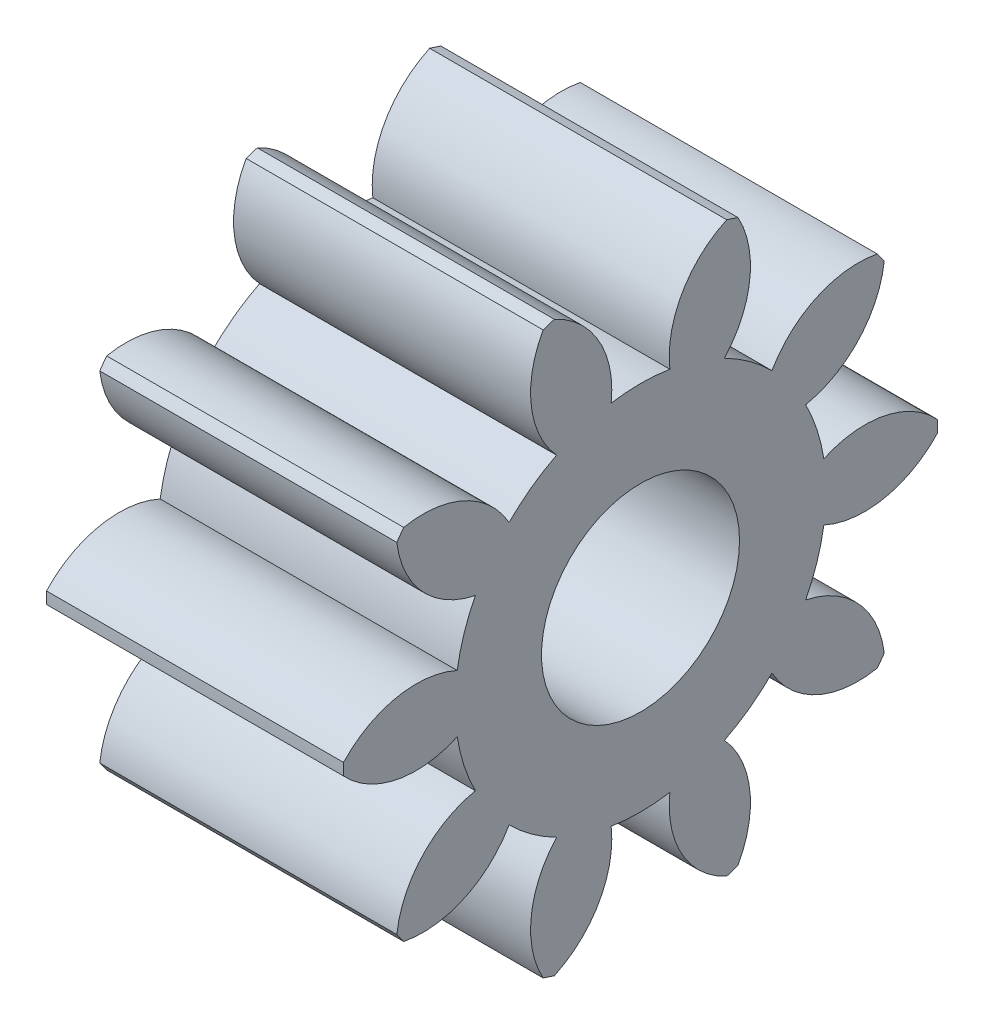
SolidWorks part; units mm, degrees
ref_plane "Plane1" through (0, 0, 0) normal (0, 0, 1) x (1, 0, 0)
ref_plane "Plane2" through (0, 0, 0) normal (0, 1, 0) x (1, 0, 0)
ref_plane "Plane3" through (0, 0, 0) normal (1, 0, 0) x (0, 0, -1)
sketch "HoldingSke" plane through (0, 0, 0) normal (0, 1, 0) x (1, 0, 0)
  line L0 (0, 0) -> (1.9696, -0.3473)
  line L1 (-15, 0) -> (100, 0) construction
  line L2 (0, 0) -> (-2.1039, 2.3779)
  line L3 (0, 0) -> (-11.863, 4.5341)
  line L4 (0, 0) -> (8.5048, 1.4996)
  line L5 (0, 0) -> (-46.8476, -17.4728)
  line L6 (0, 0) -> (-9.9476, -6.7116)
  line L7 (-2.1039, 2.3779) -> (8.6586, 51.2059)
  line L8 (-76.2, 54.61) -> (-75.9, 54.61)
  line L9 (-71.009, 38.7566) -> (-53.1078, 45.2721)
  line L10 (-76.2, 71.12) -> (104.1128, 71.12)
  line L11 (0, 0) -> (-12, 0)
  line L12 (-76.2, 101.6) -> (-76.181, 101.6)
  line L13 (24.9733, 27.94) -> (52.9518, 28.4284)
  line L14 (24.9733, 27.94) -> (24.9743, 27.94)
  line L15 (24.9733, 27.94) -> (100.4006, 29.5858)
  line L16 (-63.627, -0.5) -> (-12.827, -0.5)
  circle A0 centre (0, 0) radius 1
  circle A1 centre (0, 0) radius 1.874
  circle A2 centre (0, 0) radius 37.5
  circle A3 centre (0, 0) radius 1
  dimension "MHD" = 3.748
  dimension "Hub_dia" = 75
  dimension "Bore" = 2
  dimension "MBD" = 2
  dimension "Num_teeth" = 10
  dimension "Pitch" = 2
  dimension "Overall_len" = 50
  dimension "Show_teeth" = 10
  dimension "Thickness" = 12
  dimension "OAL" = 50.0001
  dimension "T_dim" = 0.3
  dimension "Ap" = 20
  dimension "H" = 19.05
  dimension "Pitch_radius" = 180.3128
  dimension "Width" = 12
  dimension "Backlash" = 0.019
  dimension "Addendum_fac" = 1
  dimension "Dedendum_fac" = 1.25
  dimension "Clearance_fac" = 0.25
  dimension "Dedendum_add" = 0.001
  dimension "Module" = 0.5
sketch "BasProSke" plane through (0, 0, 0) normal (0, 1, 0) x (1, 0, 0)
  line L0 (-10, 0) -> (60, 0) construction
  line L1 (0, 0) -> (0, 3)
  line L2 (0, 0) -> (12, 0)
  line L3 (12, 0) -> (12, 3)
  line L4 (12, 3) -> (0, 3)
  dimension "Thickness" = 12
  dimension "Diameter" = 6
revolve "Base-Revolve" add sketch "BasProSke" angle 360 about L0
sketch "TooCutSke" plane through (0, 0, 0) normal (1, 0, 0) x (0, 0, -1)
  line L1 (0, 0) -> (0, 107) construction
  line L2 (0, 0) -> (-0.4243, 2.4637) construction
  line L3 (0, 0) -> (-1.5292, 4.7063) construction
  line L4 (-0.4243, 2.4637) -> (-0.7646, 2.3532) construction
  arc A0 (0.2964, 1.8504) -> (-0.2964, 1.8504) centre (0, 0) ccw
  arc A1 (0.9059, 2.8866) -> (-0.9059, 2.8866) centre (0, 0) ccw
  circle A2 centre (0, 0) radius 2.5 construction
  circle A3 centre (0, 0) radius 2.3492 construction
  arc A4 (-0.2964, 1.8504) -> (-0.9059, 2.8866) centre (-1.2901, 1.9633) ccw
  arc A5 (0.9059, 2.8866) -> (0.2964, 1.8504) centre (1.2901, 1.9633) ccw
  dimension "Root_dia" = 3.748
  dimension "Overcut_dia" = 6.0508
  dimension "Pitch_dia" = 5
  dimension "Base_dia" = 4.6985
  dimension "Flank_rad" = 1
  dimension "Half_ang" = 18
  dimension "Half_CT" = 0.3578
extrude "ToothCut" cut sketch "TooCutSke" along normal through all
fillet "Breaks" [suppressed] radius 0.01
fillet "RootFillets" [suppressed] radius 0.126
pattern_circular "TeethCuts" count 10 every 36 about axis through (-10, 0, 0) along (1, 0, 0) of "ToothCut", "RootFillets", "Breaks"
sketch "HubNeaOneSke" plane through (0, 0, 0) normal (-1, 0, 0) x (0, 0, 1)
  circle A0 centre (0, 0) radius 1.874
  dimension "Diameter" = 3.748
extrude "HubNearOne" [suppressed] add sketch "HubNeaOneSke" along normal blind 38.0001
sketch "HubNeaBotSke" plane through (0, 0, 0) normal (-1, 0, 0) x (0, 0, 1)
  circle A0 centre (0, 0) radius 1.874
  dimension "Diameter" = 3.748
extrude "HubNearBoth" [suppressed] add sketch "HubNeaBotSke" along normal blind 19
ref_plane "FarPln" through (12, 0, 0) normal (1, 0, 0) x (0, 0, -1)
sketch "HubFarSke" plane through (12, 0, 0) normal (1, 0, 0) x (0, 0, -1)
  circle A0 centre (0, 0) radius 1.874
  dimension "Diameter" = 3.748
extrude "HubFar" [suppressed] add sketch "HubFarSke" along normal blind 19
sketch "BorSke" plane through (0, 0, 0) normal (1, 0, 0) x (0, 0, -1)
  circle A0 centre (0, 0) radius 1
  dimension "Diameter" = 2
extrude "Bore" cut sketch "BorSke" along normal mid plane 100.0001
sketch "KeySke" plane through (0, 0, 0) normal (1, 0, 0) x (0, 0, -1)
  line L0 (-0.4, 0) -> (-0.4, 1.3)
  line L1 (-0.4, 1.3) -> (0.4, 1.3)
  line L2 (0.4, 1.3) -> (0.4, 0)
  line L3 (0, 0) -> (0, 34) construction
  line L4 (-0.4, 0) -> (0.4, 0)
  dimension "Offset" = 1.3
  dimension "Width" = 0.8
extrude "Keyway" [suppressed] cut sketch "KeySke" along normal mid plane 100.0001
pattern_circular "Keyway2" [suppressed] count 2 every 90 about axis through (-10, 0, 0) along (1, 0, 0)
sketch "Croquis1" plane through (12, 0, 0) normal (1, 0, 0) x (0, 0, -1)
  line L1 (-3.594, 3.3455) -> (3.7696, 3.3455)
  line L2 (-3.594, 3.3455) -> (-3.594, -3.2243)
  line L3 (-3.594, -3.2243) -> (3.7696, -3.2243)
  line L4 (3.7696, 3.3455) -> (3.7696, -3.2243)
extrude "Cortar-Extruir1" cut sketch "Croquis1" against normal blind 9
equation "' \"Module@HoldingSke\" = 6.35"
equation "' \"Num_teeth@HoldingSke\" = 12"
equation "' \"Ap@HoldingSke\" =  20"
equation "' \"Ap@HoldingSke\" = 20"
equation "' \"Width@HoldingSke\" = 0.5 * 25.4"
equation "' \"Hub_dia@HoldingSke\"= 1 * 25.4"
equation "' \"Hub_dia@HoldingSke\" = 1 * 25.4"
equation "' \"Overall_len@HoldingSke\" = 1.0 * 25.4"
equation "' \"Bore@HoldingSke\" = 0.75 * 25.4"
equation "' \"T_dim@HoldingSke\" = 0.1 * 25.4"
equation "' \"Width@KeySke\" = 0.25 * 25.4"
equation "' \"Show_teeth@HoldingSke\" = 13"
equation "' \"Backlash@HoldingSke\" = 0.009 * 25.4"
equation "' \"Addendum_fac@HoldingSke\" = 1.0"
equation "' \"Dedendum_fac@HoldingSke\" = 1.25"
equation "' \"Dedendum_add@HoldingSke\" = 0.00005 * 25.4"
equation "' \"Clearance_fac@HoldingSke\" = 0.25"
equation "\"Pitch@HoldingSke\" = 1 / \"Module@HoldingSke\""
equation "\"Overcut_dia@TooCutSke\" = (\"Num_teeth@HoldingSke\" + 2 * \"Addendum_fac@HoldingSke\") / \"Pitch@HoldingSke\" + 0.002 * 25.4"
equation "\"Pitch_dia@TooCutSke\" = \"Num_teeth@HoldingSke\" / \"Pitch@HoldingSke\""
equation "\"Base_dia@TooCutSke\" = \"Num_teeth@HoldingSke\" / \"Pitch@HoldingSke\" * cos((\"Ap@HoldingSke\"  * 3.14159265 / 180))"
equation "\"Root_dia@TooCutSke\" = (\"Num_teeth@HoldingSke\" + 2) / \"Pitch@HoldingSke\" - 2 * (\"Addendum_fac@HoldingSke\" + \"Dedendum_fac@HoldingSke\") / \"Pitch@HoldingSke\" - \"Dedendum_add@HoldingSke\" * 2"
equation "\"Half_ang@TooCutSke\" = 180 / \"Num_teeth@HoldingSke\""
equation "\"Half_CT@TooCutSke\" = \"Num_teeth@HoldingSke\" / \"Pitch@HoldingSke\" * sin((3.14159265 / 2 / \"Num_teeth@HoldingSke\")) / 2 - 7 * \"Backlash@HoldingSke\" / 4"
equation "\"Flank_rad@TooCutSke\" = \"Num_teeth@HoldingSke\" / \"Pitch@HoldingSke\" / 5"
equation "\"Radius@RootFillets\" = \"Clearance_fac@HoldingSke\" / \"Pitch@HoldingSke\" + \"Dedendum_add@HoldingSke\""
equation "\"Break_rad@Breaks\" = 0.02 / \"Pitch@HoldingSke\""
equation "\"Thickness@HoldingSke\" = \"Width@HoldingSke\""
equation "\"OAL@HoldingSke\" = \"Thickness@HoldingSke\""
equation "\"MHD@HoldingSke\" = (\"Num_teeth@HoldingSke\" + 2) / \"Pitch@HoldingSke\" - 2 * (\"Addendum_fac@HoldingSke\" + \"Dedendum_fac@HoldingSke\")  / \"Pitch@HoldingSke\" - \"Dedendum_add@HoldingSke\" * 2"
equation "\"MBD@HoldingSke\" = (\"Num_teeth@HoldingSke\" + 2) / \"Pitch@HoldingSke\" - 2 * (\"Addendum_fac@HoldingSke\" + \"Dedendum_fac@HoldingSke\")  / \"Pitch@HoldingSke\" - \"Dedendum_add@HoldingSke\" * 2 - 0.002 * 25.4"
equation "\"MHD@HoldingSke\" = ((sgn( \"MHD@HoldingSke\" - \"Hub_dia@HoldingSke\" )-1)*( \"MHD@HoldingSke\" - \"Hub_dia@HoldingSke\" ))/-2+ \"Hub_dia@HoldingSke\""
equation "\"MBD@HoldingSke\" = ((sgn( \"MBD@HoldingSke\" - \"Bore@HoldingSke\" )-1)*( \"MBD@HoldingSke\" - \"Bore@HoldingSke\" ))/-2+ \"Bore@HoldingSke\""
equation "\"OAL@HoldingSke\" = ((sgn( \"OAL@HoldingSke\" - \"Overall_len@HoldingSke\" )+1)*( \"OAL@HoldingSke\" - \"Overall_len@HoldingSke\" ))/2 + \"Overall_len@HoldingSke\" + 0.000002 * 25.4"
equation "\"Num_teeth@TeethCuts\" = int( \"Show_teeth@HoldingSke\" ) + 1"
equation "\"Num_teeth@TeethCuts\" = ((sgn( \"Num_teeth@TeethCuts\" - \"Num_teeth@HoldingSke\" )-1)*( \"Num_teeth@TeethCuts\" - \"Num_teeth@HoldingSke\" ))/-2+ \"Num_teeth@HoldingSke\""
equation "\"Num_teeth@TeethCuts\" = ((sgn( \"Num_teeth@TeethCuts\" - 2.0)+1)*( \"Num_teeth@TeethCuts\" - 2.0))/2 +2.0"
equation "\"Angle@TeethCuts\" = 360.0 / \"Num_teeth@HoldingSke\""
equation "\"Diameter@BasProSke\" = (\"Num_teeth@HoldingSke\" + 2 * \"Addendum_fac@HoldingSke\") / \"Pitch@HoldingSke\""
equation "\"Thickness@BasProSke\"  = \"Thickness@HoldingSke\""
equation "' \"Fillet_rad@BasProSke\" =  \"Thickness@HoldingSke\" * 0.05"
equation "' \"Fillet_rad@BasProSke\" = \"Thickness@HoldingSke\" * 0.05"
equation "\"MHD@HoldingSke\" = ((sgn( \"MHD@HoldingSke\" - \"Root_dia@TooCutSke\" )-1)*( \"MHD@HoldingSke\" - \"Root_dia@TooCutSke\" ))/-2+ \"Root_dia@TooCutSke\""
equation "\"Diameter@HubNeaOneSke\" = \"MHD@HoldingSke\""
equation "\"Length@HubNearOne\" = \"OAL@HoldingSke\" - \"Thickness@BasProSke\""
equation "\"Diameter@HubNeaBotSke\" = \"MHD@HoldingSke\""
equation "\"Length@HubNearBoth\" = ( \"OAL@HoldingSke\" - \"Thickness@BasProSke\" ) / 2.0"
equation "\"Thickness@FarPln\" = \"Thickness@BasProSke\""
equation "\"Diameter@HubFarSke\" = \"MHD@HoldingSke\""
equation "\"Length@HubFar\" = ( \"OAL@HoldingSke\" - \"Thickness@BasProSke\" ) / 2.0"
equation "\"Diameter@BorSke\" = \"MBD@HoldingSke\""
equation "\"D1@Bore\" = \"OAL@HoldingSke\" * 2.0"
equation "\"D1@Keyway\" = \"OAL@HoldingSke\" * 2.0"
equation "\"Offset@KeySke\" = \"T_dim@HoldingSke\" + \"MBD@HoldingSke\" / 2.0"
